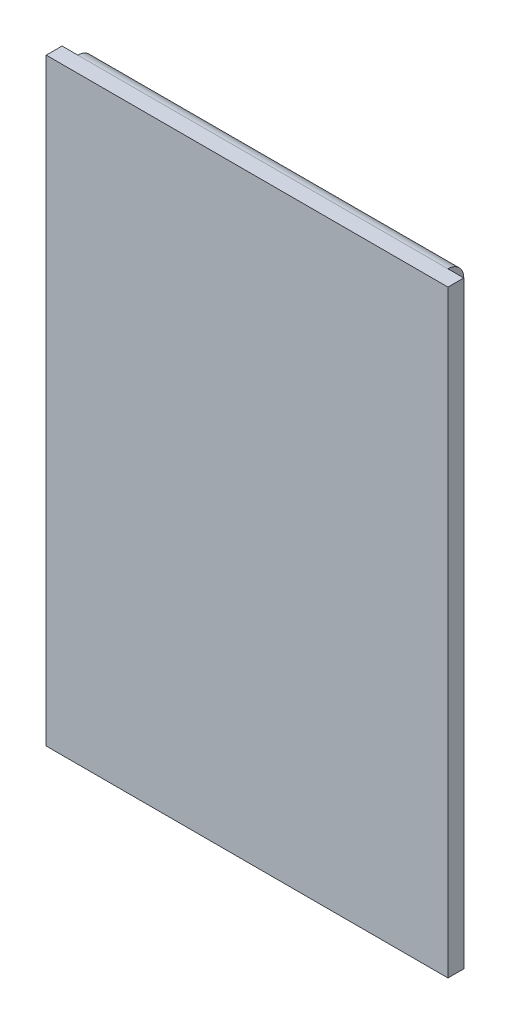
SolidWorks part; units mm, degrees
ref_plane "Front Plane" through (0, 0, 0) normal (0, 0, 1) x (1, 0, 0)
ref_plane "Top Plane" through (0, 0, 0) normal (0, 1, 0) x (1, 0, 0)
ref_plane "Right Plane" through (0, 0, 0) normal (1, 0, 0) x (0, 0, -1)
sketch "Sketch1" plane through (0, 0, 0) normal (0, 1, 0) x (1, 0, 0)
  line L1 (-19.2072, 15.2837) -> (27.5928, 15.2837)
  line L2 (-21.2072, 13.2837) -> (-21.2072, 11.2837)
  line L3 (-21.2072, 11.2837) -> (29.5928, 11.2837)
  line L4 (29.5928, 13.2837) -> (29.5928, 11.2837)
  line L7 (-21.2072, 13.2837) -> (-19.2072, 13.2837)
  line L8 (-19.2072, 15.2837) -> (-19.2072, 13.2837)
  line L11 (29.5928, 13.2837) -> (27.5928, 13.2837)
  line L12 (27.5928, 15.2837) -> (27.5928, 13.2837)
  dimension "D1" = 2
  dimension "D2" = 2
  dimension "D3" = 2
  dimension "D4" = 2
  dimension "D5" = 2
  dimension "D6" = 2
  dimension "D7" = 46.8
extrude "Boss-Extrude2" add sketch "Sketch1" along normal blind 75.66
sketch "Sketch2" plane through (27.5928, 0, 0) normal (1, 0, 0) x (0, 0, -1)
  line L0 (13.2837, 75.66) -> (13.2837, 0) construction
  line L1 (15.2837, 0) -> (13.2837, 0)
  line L2 (15.2837, 0) -> (15.2837, 2)
  line L3 (15.2837, 2) -> (13.2837, 2)
  line L4 (13.2837, 0) -> (13.2837, 2)
  dimension "D1" = 2
extrude "Cut-Extrude2" cut sketch "Sketch2" against normal blind 69
fillet "Fillet1" radius 2 1 edges at (4.1928, 75.66, -15.2837)
sketch "Sketch3" plane through (0, 0, -15.2837) normal (0, 0, -1) x (-1, 0, 0)
  line L0 (19.2072, 73.66) -> (19.2072, 2) construction
  line L1 (-8.3857, 73.4413) -> (2.6143, 73.4413)
  line L3 (-8.3857, 71.4413) -> (2.6143, 71.4413)
  line L5 (-8.3857, 73.4413) -> (2.6143, 71.608) construction
  line L6 (-8.3857, 71.4413) -> (2.6143, 73.2746) construction
  line L7 (2.6143, 73.4413) -> (-9.3857, 73.4413)
  line L8 (2.6143, 73.4413) -> (2.6143, 71.4413)
  line L9 (2.6143, 71.4413) -> (-9.3857, 71.4413)
  line L10 (-9.3857, 73.4413) -> (-9.3857, 71.4413)
  point P0 (-2.3857, 72.4413)
  point P1 (2.6143, 72.4413)
  dimension "D1" = 16.5928
  dimension "D2" = 12
extrude "Boss-Extrude5" add sketch "Sketch3" along normal blind 1 contours L7 L10 L9 L3 L8 L1
